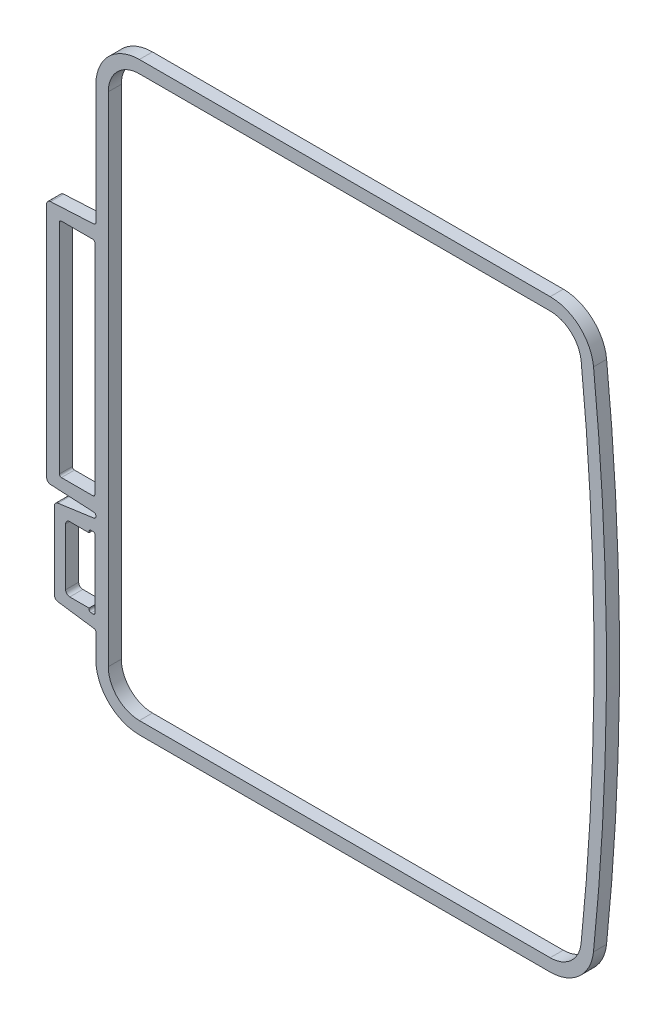
SolidWorks part; units mm, degrees
ref_plane "Front" through (0, 0, 0) normal (0, 0, 1) x (1, 0, 0)
ref_plane "Top" through (0, 0, 0) normal (0, 1, 0) x (1, 0, 0)
ref_plane "Right" through (0, 0, 0) normal (1, 0, 0) x (0, 0, -1)
sketch "Sketch1" plane through (0, 0, 0) normal (0, 0, 1) x (1, 0, 0)
  line L0 (5.334, 70.1259) -> (55.6555, 70.1259)
  line L1 (5.334, 1.524) -> (55.6464, 1.524)
  line L3 (0, 51.4198) -> (-6.0274, 51.1039)
  line L4 (-6.0274, 51.1039) -> (-6.0274, 21.1465)
  line L5 (-6.0274, 21.1465) -> (0, 20.8306)
  line L6 (0, 20.2464) -> (-5.08, 19.5324)
  line L7 (-5.08, 19.5324) -> (-5.08, 9.195)
  line L8 (-5.08, 9.195) -> (0, 8.4811)
  line L9 (-0.127, 49.7282) -> (-4.4704, 49.7282)
  line L10 (5.334, 0) -> (55.6464, 0)
  line L11 (0, 66.3159) -> (0, 51.4198)
  line L12 (5.334, 71.6499) -> (55.6555, 71.6499)
  line L13 (-4.4704, 49.7282) -> (-4.4704, 22.5222)
  line L14 (-4.4704, 22.5222) -> (-0.127, 22.5222)
  line L15 (-0.8382, 18.3566) -> (-3.7033, 18.3566)
  line L16 (-3.7033, 18.3566) -> (-3.7033, 10.3734)
  line L17 (-3.7033, 10.3734) -> (-0.8382, 10.3734)
  line L18 (-0.127, 49.7282) -> (-0.127, 22.5222)
  line L19 (0, 66.3159) -> (0, 5.334) construction
  line L20 (0, 20.8306) -> (0, 20.2464)
  line L21 (-0.0762, 18.7376) -> (-0.0762, 9.9924)
  line L22 (0, 8.4811) -> (0, 5.334)
  line L26 (-0.0762, 18.7376) -> (-0.8382, 18.7376)
  line L27 (-0.8382, 18.3566) -> (-0.8382, 18.7376)
  line L30 (-0.0762, 9.9924) -> (-0.8382, 9.9924)
  line L31 (-0.8382, 10.3734) -> (-0.8382, 9.9924)
  line L35 (1.524, 66.3159) -> (1.524, 5.334)
  line L38 (1.524, 66.3159) -> (1.524, 5.334) construction
  arc A0 (55.6555, 70.1259) -> (59.4457, 66.7035) centre (55.6555, 66.3159) cw
  arc A1 (59.4365, 4.9453) -> (59.4457, 66.7035) centre (-242.0607, 35.8694) ccw
  arc A2 (55.6464, 1.524) -> (59.4365, 4.9453) centre (55.6464, 5.334) ccw
  arc A3 (1.524, 5.334) -> (5.334, 1.524) centre (5.334, 5.334) ccw
  arc A4 (5.334, 70.1259) -> (1.524, 66.3159) centre (5.334, 66.3159) ccw
  arc A10 (55.6555, 71.6499) -> (60.9618, 66.8586) centre (55.6555, 66.3159) cw
  arc A11 (60.9526, 4.7898) -> (60.9618, 66.8586) centre (-242.0607, 35.8694) ccw
  arc A12 (55.6464, 0) -> (60.9526, 4.7898) centre (55.6464, 5.334) ccw
  arc A13 (0, 5.334) -> (5.334, 0) centre (5.334, 5.334) ccw
  arc A14 (5.334, 71.6499) -> (0, 66.3159) centre (5.334, 66.3159) ccw
  dimension "D2" = 35.7805
  dimension "D4" = 242.0607
  dimension "D5" = 5.334
  dimension "D6" = 304.603
  dimension "D1" = 1.524
  dimension "D3" = 71.6499
  dimension "D7" = 98
  dimension "D8" = 98
  dimension "D9" = 93
  dimension "D10" = 93
  dimension "D11" = 27.2059
  dimension "D12" = 1.6916
  dimension "D13" = 30.5892
  dimension "D14" = 6.0274
  dimension "D15" = 4.3434
  dimension "D16" = 3.6271
  dimension "D17" = 8.7452
  dimension "D18" = 1.5113
  dimension "D19" = 5.08
  dimension "D20" = 8.4811
  dimension "D21" = 0.5842
  dimension "D22" = 11.7653
  dimension "D24" = 0.381
  dimension "D25" = 0.381
  dimension "D26" = 0.762
  dimension "D27" = 0.762
  dimension "D28" = 1.651
  dimension "D29" = 1.6002
extrude "Boss-Extrude1" add sketch "Sketch1" along normal blind 1.6002
fillet "Fillet1" radius 0.508 2 edges at (-3.7033, 18.3566, 0.8001) (-3.7033, 10.3734, 0.8001)
fillet "Fillet2" radius 0.508 4 edges at (-6.0274, 51.1039, 0.8001) (-6.0274, 21.1465, 0.8001) (-5.08, 19.5324, 0.8001) (-5.08, 9.195, 0.8001)
fillet "Fillet3" radius 0.254 12 edges at (0, 8.4811, 0.8001) (0, 20.8306, 0.8001) (0, 20.2464, 0.8001) (-0.127, 22.5222, 0.8001) (-4.4704, 22.5222, 0.8001) (-0.127, 49.7282, 0.8001) (-4.4704, 49.7282, 0.8001) (-0.8382, 9.9924, 0.8001) (-0.8382, 18.7376, 0.8001) (0, 51.4198, 0.8001) (-0.0762, 18.7376, 0.8001) (-0.0762, 9.9924, 0.8001)
sketch "Sketch3" plane through (0, 0, 1.6002) normal (0, 0, 1) x (1, 0, 0)
  line L0 (1.524, 35.8249) -> (14.8136, 35.8249) construction
  line L1 (1.524, 66.3159) -> (1.524, 5.334) construction
ref_plane "Plane1" through (0, 35.8249, 0) normal (0, 1, 0) x (1, 0, 0)
